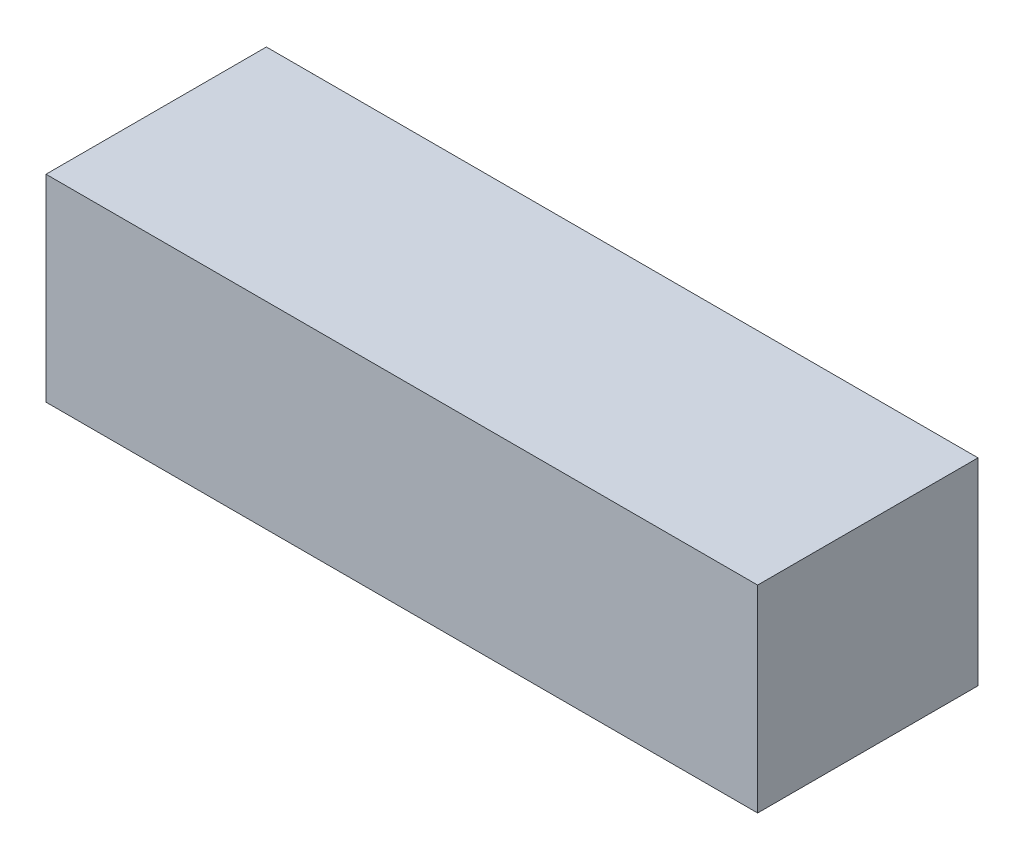
SolidWorks part; units mm, degrees
material "Manual Density from Real Component Mass Battery"
ref_plane "Piano frontale" through (0, 0, 0) normal (0, 0, 1) x (1, 0, 0)
ref_plane "Piano superiore" through (0, 0, 0) normal (0, 1, 0) x (1, 0, 0)
ref_plane "Piano destro" through (0, 0, 0) normal (1, 0, 0) x (0, 0, -1)
sketch "Schizzo1" plane through (0, 0, 0) normal (0, 1, 0) x (1, 0, 0)
  line L1 (77.5, 24) -> (-77.5, 24)
  line L2 (77.5, 24) -> (77.5, -24)
  line L3 (77.5, -24) -> (-77.5, -24)
  line L4 (-77.5, 24) -> (-77.5, -24)
  line L5 (-55, 0) -> (55, 0) construction
  line L6 (0, -55) -> (0, 55) construction
  point P4 (0, 24)
  point P6 (-77.5, 0)
  dimension "D1" = 48
  dimension "D2" = 155
extrude "Estrusione-Estrusione1" add sketch "Schizzo1" along normal blind 43
